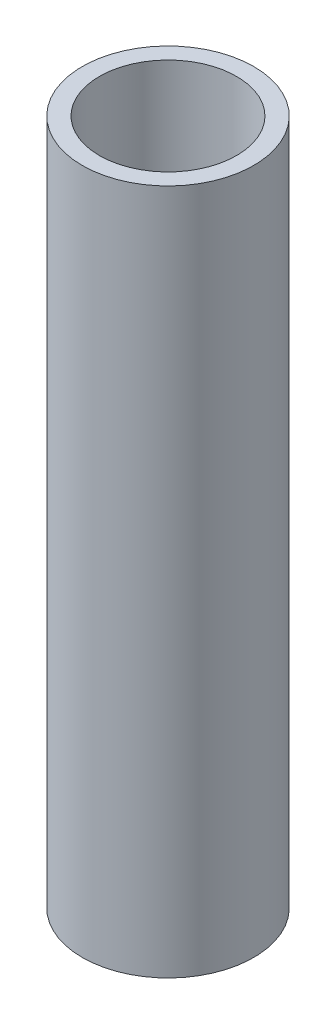
SolidWorks part; units mm, degrees
ref_plane "Front Plane" through (0, 0, 0) normal (0, 0, 1) x (1, 0, 0)
ref_plane "Top Plane" through (0, 0, 0) normal (0, 1, 0) x (1, 0, 0)
ref_plane "Right Plane" through (0, 0, 0) normal (1, 0, 0) x (0, 0, -1)
sketch "Sketch1" plane through (0, 0, 0) normal (0, 1, 0) x (1, 0, 0)
  circle A0 centre (0, 0) radius 12.5
  circle A1 centre (0, 0) radius 10
  dimension "D1" = 25
  dimension "D2" = 20
extrude "Boss-Extrude1" add sketch "Sketch1" along normal blind 100
